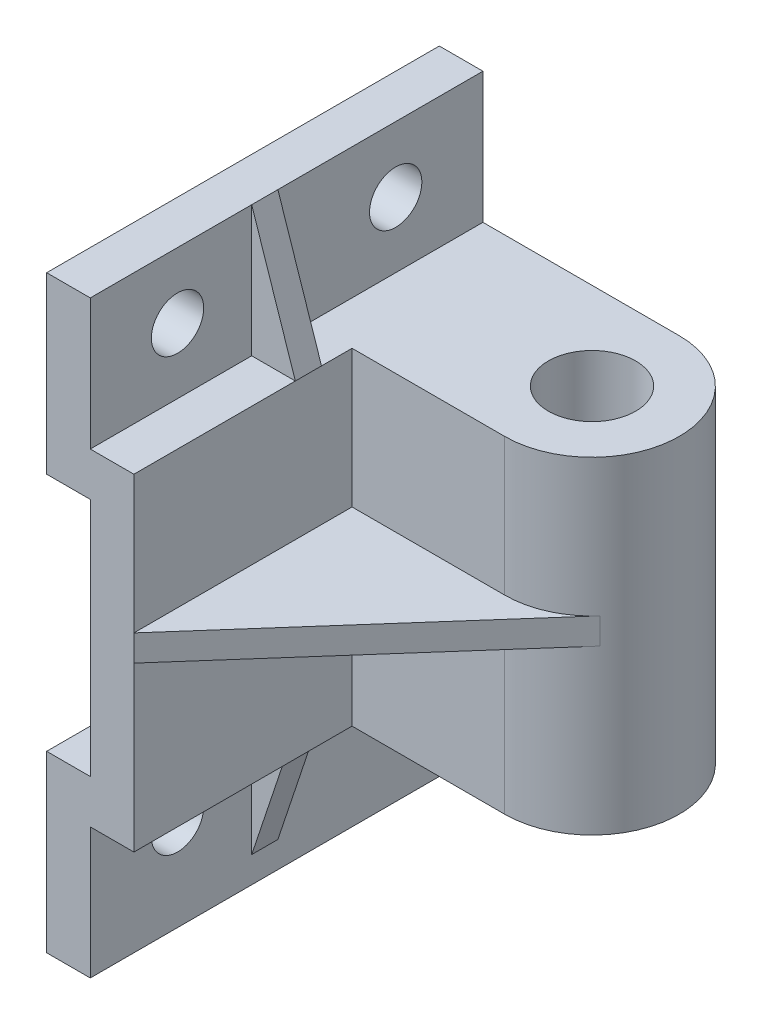
SolidWorks part; units mm, degrees
ref_plane "Ön Düzlem" through (0, 0, 0) normal (0, 0, 1) x (1, 0, 0)
ref_plane "Üst Düzlem" through (0, 0, 0) normal (0, 1, 0) x (1, 0, 0)
ref_plane "Sağ Düzlem" through (0, 0, 0) normal (1, 0, 0) x (0, 0, -1)
sketch "Çizim2" plane through (0, 0, 0) normal (0, 0, 1) x (1, 0, 0)
  line L0 (0, 0) -> (10, 0)
  line L1 (10, 0) -> (10, 30)
  line L2 (10, 30) -> (20, 30)
  line L3 (20, 30) -> (20, 105)
  line L4 (20, 105) -> (10, 105)
  line L5 (10, 105) -> (10, 135)
  line L6 (10, 135) -> (0, 135)
  line L7 (0, 135) -> (0, 95)
  line L8 (0, 95) -> (10, 95)
  line L9 (10, 95) -> (10, 40)
  line L10 (10, 40) -> (0, 40)
  line L11 (0, 40) -> (0, 0)
  point P2 (0, 0)
  point P14 (0, 0)
  dimension "D1" = 10
  dimension "D2" = 10
  dimension "D3" = 55
  dimension "D4" = 10
  dimension "D5" = 10
  dimension "D6" = 10
  dimension "D7" = 135
  dimension "D8" = 40
  dimension "D9" = 10
extrude "Yükseklik-Ekstrüzyon1" add sketch "Çizim2" against normal blind 90
sketch "Çizim3" plane through (0, 105, 0) normal (0, 1, 0) x (1, 0, 0)
  line L0 (20, 90) -> (55, 90)
  line L1 (55, 50) -> (20, 50)
  line L2 (20, 90) -> (20, 0) construction
  line L3 (20, 50) -> (20, 90)
  arc A0 (55, 50) -> (55, 90) centre (55, 70) ccw
  circle A1 centre (55, 70) radius 10
  dimension "D2" = 40
  dimension "D3" = 20
extrude "Yükseklik-Ekstrüzyon2" add sketch "Çizim3" against normal up to surface (75 mm away) up to face at (15, 30, -45)
sketch "Çizim5" plane through (0, 105, 0) normal (0, 1, 0) x (1, 0, 0)
  line L0 (20, 0) -> (70.0089, 56.7813)
  line L6 (10, 0) -> (20, 0)
  line L7 (20, 0) -> (20, 50)
  line L8 (20, 50) -> (55, 50)
  line L9 (55, 90) -> (10, 90)
  line L10 (10, 90) -> (10, 0)
  line L12 (20, 0) -> (20, 50)
  line L13 (20, 50) -> (55, 50)
  arc A0 (55, 50) -> (55, 90) centre (55, 70) ccw construction
  arc A2 (55, 50) -> (55, 90) centre (55, 70) ccw
  arc A3 (55, 50) -> (70.0089, 56.7813) centre (55, 70) ccw
  point P6 (0, 0)
  dimension "D1" = 0
extrude "Yükseklik-Ekstrüzyon3" add sketch "Çizim5" along normal blind 6 from offset 37.5 separate body offset against normal yes
sketch "Çizim7" plane through (0, 0, 0) normal (0, 0, 1) x (1, 0, 0)
  line L0 (10, 135) -> (20, 105)
  line L1 (20, 105) -> (10, 105)
  line L2 (10, 105) -> (10, 135)
extrude "Yükseklik-Ekstrüzyon4" add sketch "Çizim7" against normal blind 6 from offset 37 offset against normal yes
sketch "Çizim8" plane through (20, 0, 0) normal (1, 0, 0) x (0, 0, -1)
  line L0 (0, 70.5) -> (121.2105, 70.5) construction
  line L1 (0, 73.5) -> (0, 67.5) construction
ref_plane "Düzlem1" through (0, 70.5, 0) normal (0, 1, 0) x (1, 0, 0)
mirror "Aynalama5" about plane through (0, 70.5, 0) normal (0, 1, 0) of "Yükseklik-Ekstrüzyon4"
hole_wizard "Ø12.0 (12) Çap Delik1" positions "3B Çizim1" profile "Çizim10" hole size "Ø12.0" standard "ANSI Metric"
sketch3d "3B Çizim1"
  line L0 (10, 105, 0) -> (10, 135, 0) construction
  line L1 (10, 105, -37) -> (10, 105, 0) construction
  line L2 (10, 105, -90) -> (10, 105, -43) construction
  point P0 (10, 120, -20)
  point P2 (10, 120, -70)
  point P10 (0, 0, 0)
  point P11 (0, 0, 0)
  dimension "D1" = 20
  dimension "D2" = 70
  dimension "D3" = 15
  dimension "D4" = 15
sketch "Çizim10" plane through (10, 120, -20) normal (0, 1, 0) x (0, 0, -1)
  line L0 (0, 0) -> (0, 13.6052)
  line L1 (0, 13.6052) -> (6, 10)
  line L2 (6, 10) -> (6, 0)
  line L5 (6, 0) -> (0, 0)
  line L10 (0, 13.6052) -> (-6, 10) construction
  line L11 (0, -6.35) -> (0, 107.95) construction
  dimension "Hole Dia." = 12
  dimension "Hole Depth" = 10
  dimension "Drill Angle" = 118
mirror "Aynalama6" about plane through (0, 70.5, 0) normal (0, 1, 0) of "Ø12.0 (12) Çap Delik1"
